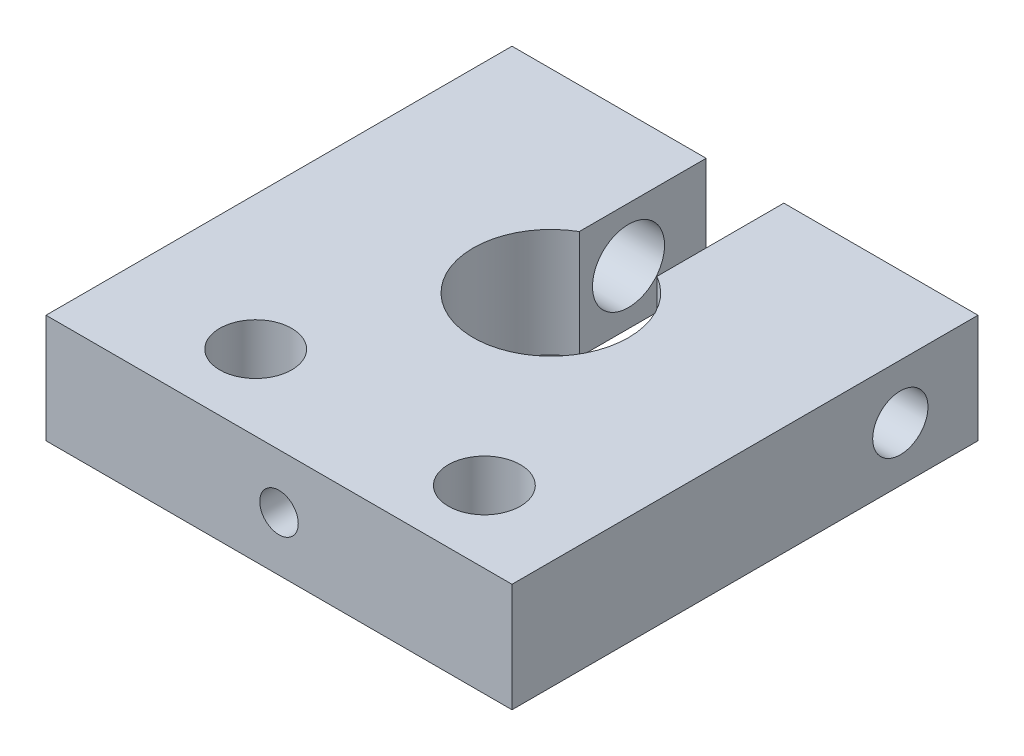
SolidWorks part; units mm, degrees
ref_plane "Front Plane" through (0, 0, 0) normal (0, 0, 1) x (1, 0, 0)
ref_plane "Top Plane" through (0, 0, 0) normal (0, 1, 0) x (1, 0, 0)
ref_plane "Right Plane" through (0, 0, 0) normal (1, 0, 0) x (0, 0, -1)
sketch "Sketch1" plane through (0, 0, 0) normal (0, 1, 0) x (1, 0, 0)
  line L1 (-9.525, -11.1125) -> (9.525, -11.1125)
  line L2 (-9.525, -11.1125) -> (-9.525, 7.9375)
  line L3 (-9.525, 7.9375) -> (9.525, 7.9375)
  line L4 (9.525, -11.1125) -> (9.525, 7.9375)
  circle A0 centre (0, 0) radius 3.175
  point P7 (0, -11.1125)
  dimension "D1" = 6.35
  dimension "D4" = 11.1125
  dimension "D2" = 19.05
  dimension "D3" = 19.05
extrude "Boss-Extrude1" add sketch "Sketch1" along normal blind 4.445
sketch "Sketch2" plane through (0, 4.445, 0) normal (0, 1, 0) x (1, 0, 0)
  line L0 (9.525, 7.9375) -> (-9.525, 7.9375) construction
  line L1 (-1.5875, 7.9375) -> (1.5875, 7.9375)
  line L2 (-1.5875, 7.9375) -> (-1.5875, 2.7496)
  line L3 (-1.5875, 2.7496) -> (1.5875, 2.7496)
  line L4 (1.5875, 7.9375) -> (1.5875, 2.7496)
  circle A0 centre (0, 0) radius 3.175 construction
  circle A1 centre (5.461, -8.1788) radius 1.4732
  circle A2 centre (-4.0386, -8.0264) radius 1.4732
  point P9 (0, 7.9375)
  dimension "D2" = 2.9464
  dimension "D4" = 5.461
  dimension "D5" = 2.9464
  dimension "D7" = 8.0264
  dimension "D1" = 3.175
  dimension "D3" = 8.1788
  dimension "D6" = 4.0386
extrude "Cut-Extrude1" cut sketch "Sketch2" against normal through all
sketch "Sketch4" plane through (0, 0, 11.1125) normal (0, 0, 1) x (1, 0, 0)
  line L0 (9.525, 4.445) -> (9.525, 0) construction
  circle A0 centre (0, 2.2225) radius 0.7874
  point P5 (9.525, 2.2225)
  dimension "D1" = 1.5748
extrude "Cut-Extrude3" cut sketch "Sketch4" against normal through all
sketch "Sketch6" plane through (0, 0, 0) normal (1, 0, 0) x (0, 0, -1)
  line L0 (7.9375, 4.445) -> (7.9375, 0) construction
  line L1 (-11.1125, 3.0099) -> (-11.1125, 1.4351) construction
  circle A0 centre (4.7625, 2.2225) radius 1.1303
  point P4 (7.9375, 2.2225)
  dimension "D1" = 2.2606
  dimension "D2" = 15.875
extrude "Cut-Extrude5" cut sketch "Sketch6" along normal through all
sketch "Sketch7" plane through (0, 0, 0) normal (1, 0, 0) x (0, 0, -1)
  circle A0 centre (4.7625, 2.2225) radius 1.4732
  dimension "D1" = 2.9464
extrude "Cut-Extrude6" cut sketch "Sketch7" against normal through all
